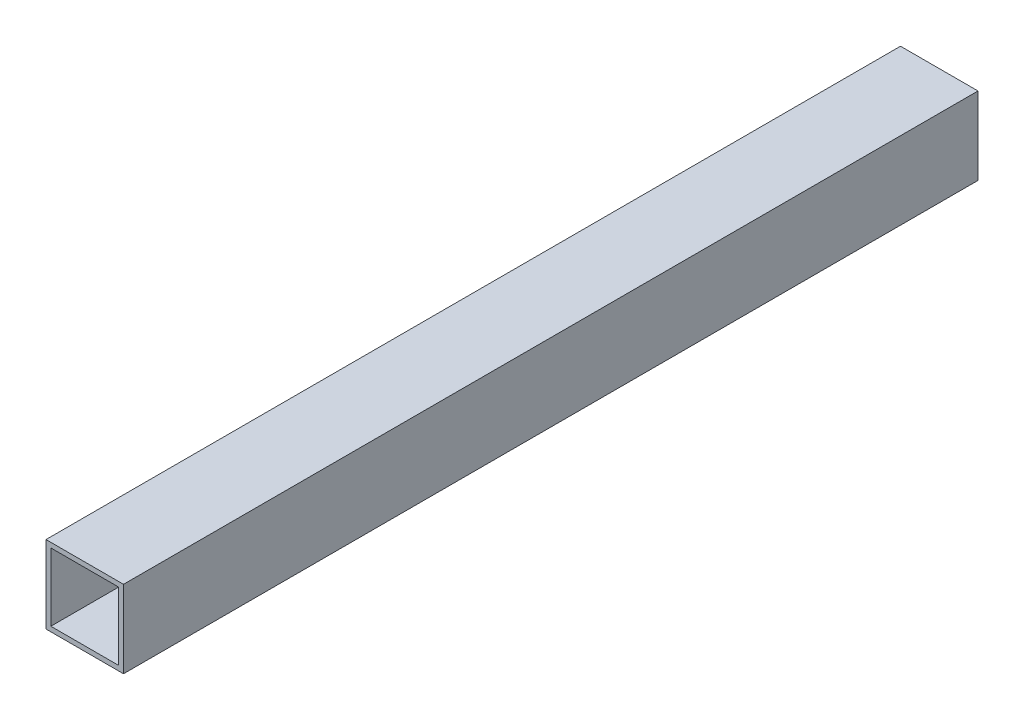
SolidWorks part; units mm, degrees
ref_plane "Front Plane" through (0, 0, 0) normal (0, 0, 1) x (1, 0, 0)
ref_plane "Top Plane" through (0, 0, 0) normal (0, 1, 0) x (1, 0, 0)
ref_plane "Right Plane" through (0, 0, 0) normal (1, 0, 0) x (0, 0, -1)
sketch "Sketch1" plane through (0, 0, 0) normal (0, 0, 1) x (1, 0, 0)
  line L1 (-11.1125, -11.1125) -> (11.1125, -11.1125)
  line L2 (-11.1125, -11.1125) -> (-11.1125, 11.1125)
  line L3 (-11.1125, 11.1125) -> (11.1125, 11.1125)
  line L4 (11.1125, -11.1125) -> (11.1125, 11.1125)
  line L5 (-11.1125, -11.1125) -> (11.1125, 11.1125) construction
  line L6 (-11.1125, 11.1125) -> (11.1125, -11.1125) construction
  line L7 (-12.7, -12.7) -> (12.7, -12.7)
  line L8 (-12.7, -12.7) -> (-12.7, 12.7)
  line L9 (-12.7, 12.7) -> (12.7, 12.7)
  line L10 (12.7, -12.7) -> (12.7, 12.7)
  line L11 (-12.7, -12.7) -> (12.7, 12.7) construction
  line L12 (-12.7, 12.7) -> (12.7, -12.7) construction
  point P0 (0, 0)
  point P6 (0, 0)
  dimension "D1" = 25.4
  dimension "D2" = 1.5875
extrude "Boss-Extrude1" add sketch "Sketch1" along normal blind 280
